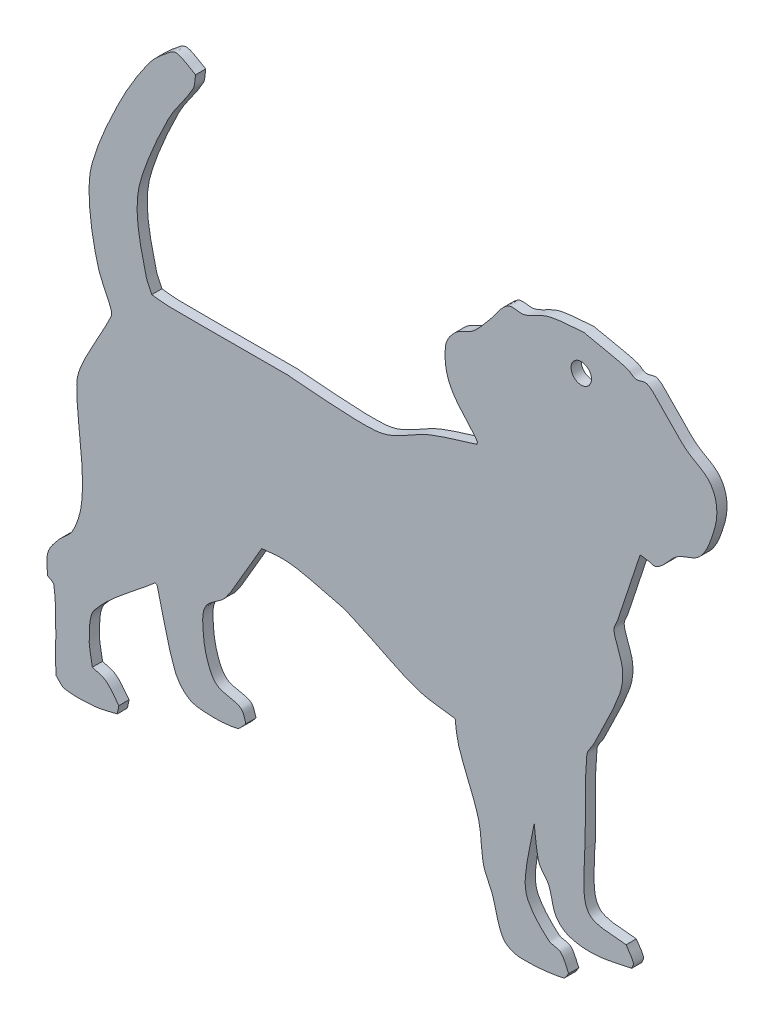
SolidWorks part; units mm, degrees
material "Custom Plastic"
ref_plane "Front Plane" through (0, 0, 0) normal (0, 0, 1) x (1, 0, 0)
ref_plane "Top Plane" through (0, 0, 0) normal (0, 1, 0) x (1, 0, 0)
ref_plane "Right Plane" through (0, 0, 0) normal (1, 0, 0) x (0, 0, -1)
sketch "Sketch1" plane through (0, 0, 0) normal (0, 0, 1) x (1, 0, 0)
  line L0 (320, 883) -> (1600, 883) construction
  line L1 (430, 467) -> (425, 468)
  line L2 (335, 158) -> (331, 138)
  spline S0 degree 3 poles (157, 350) (157.3333, 366.6667) (153.3255, 383.9988) (158, 400) (162.3301, 414.8221) (173.3915, 426.9119) (183, 439) (194.1503, 453.0279) (211.409, 462.2741) (220, 478) (231.5736, 499.1856) (238.9889, 523.0477) (242, 547) (246.5737, 583.3818) (244.0243, 620.4567) (241, 657) (237.1118, 703.9822) (229.509, 750.8597) (230, 798) (230.1827, 815.5426) (235.7972, 833.0032) (243, 849) (264.6078, 896.9895) (293.9451, 941.2143) (316, 989) (318.2393, 993.8519) (316.8218, 999.9764) (315, 1005) (305.7338, 1030.5522) (290.1289, 1053.7711) (283, 1080) (272.3494, 1119.1863) (264.8394, 1159.4915) (262, 1200) (259.8047, 1231.3203) (259.4994, 1263.7756) (268, 1294) (283.787, 1350.1317) (308.2885, 1403.6653) (334, 1456) (355.4262, 1499.6122) (380.5007, 1541.6439) (409, 1581) (422.8269, 1600.0943) (441.5162, 1615.367) (460, 1630) (465.8731, 1634.6495) (473.6955, 1639.6601) (481, 1638) (497.4268, 1634.2666) (511, 1622.6667) (526, 1615) knots 0 0 0 0 1 1 1 2 2 2 3 3 3 4 4 4 5 5 5 6 6 6 7 7 7 8 8 8 9 9 9 10 10 10 11 11 11 12 12 12 13 13 13 14 14 14 15 15 15 16 16 16 17 17 17 17
  spline S1 degree 3 poles (526, 1615) (524, 1604) (525.1849, 1591.9054) (520, 1582) (502.5479, 1548.6586) (475.8299, 1520.6597) (459, 1487) (432.3392, 1433.6783) (407.6914, 1378.9299) (390, 1322) (381.4465, 1294.4752) (379.1669, 1264.7649) (381, 1236) (383.5446, 1196.0699) (393.6625, 1156.9063) (403, 1118) (405.7171, 1106.6787) (412.3333, 1096.6667) (417, 1086) knots 0 0 0 0 1 1 1 2 2 2 3 3 3 4 4 4 5 5 5 6 6 6 6
  spline S2 degree 3 poles (417, 1086) (430, 1084.6667) (442.9327, 1082.1533) (456, 1082) (556.6597, 1080.8192) (657.3339, 1082.329) (758, 1082) (759.3744, 1081.9955) (760.6274, 1081.0702) (762, 1081) (832.3203, 1077.4022) (902.6992, 1067.0394) (973, 1071) (1022.6427, 1073.7968) (1063.7124, 1111.843) (1110, 1130) (1148.1735, 1144.9742) (1188, 1155.3333) (1227, 1168) knots 0 0 0 0 1 1 1 2 2 2 3 3 3 4 4 4 5 5 5 6 6 6 6
  spline S3 degree 3 poles (1227, 1168) (1227.3333, 1170.3333) (1229.3585, 1173.0738) (1228, 1175) (1206.6346, 1205.2942) (1175.93, 1229.5268) (1160, 1263) (1148.7167, 1286.7093) (1146.1485, 1314.898) (1149, 1341) (1150.7197, 1356.7423) (1161.6412, 1370.9657) (1173, 1382) (1185.7529, 1394.3885) (1205.2893, 1397.6807) (1219, 1409) (1234.2854, 1421.6193) (1245.8602, 1438.1597) (1259, 1453) (1274.1956, 1470.1621) (1284.5241, 1492.9115) (1304, 1505) (1315.9084, 1512.3914) (1332.4841, 1503.2898) (1346, 1507) (1367.0195, 1512.77) (1384.8286, 1527.8152) (1406, 1533) (1434.3531, 1539.9436) (1463.9508, 1540.127) (1493, 1543) (1494.3677, 1543.1353) (1495.6551, 1542.2831) (1497, 1542) (1520.9894, 1536.9496) (1545.0899, 1532.4136) (1569, 1527) (1580.4343, 1524.4111) (1592.0061, 1522.0718) (1603, 1518) (1610.1348, 1515.3575) (1615.4909, 1508.226) (1623, 1507) (1632.5913, 1505.4341) (1643.1481, 1514.011) (1652, 1510) (1666.3987, 1503.4756) (1675.5844, 1488.9349) (1687, 1478) (1707.2559, 1458.597) (1725.497, 1437.0111) (1747, 1419) (1764.6486, 1404.2174) (1788.2409, 1396.7824) (1804, 1380) (1814.821, 1368.4763) (1821.6551, 1352.633) (1824, 1337) (1826.8293, 1318.1381) (1824.5313, 1298.2533) (1819, 1280) (1810.9992, 1253.5974) (1802.3044, 1225.6412) (1784, 1205) (1769.2599, 1188.3782) (1743.0901, 1186.8959) (1725, 1174) (1709.0689, 1162.6432) (1699.0859, 1144.1364) (1683, 1133) (1666.1354, 1121.3245) (1666.2267, 1128.4267) (1656, 1130) (1648.6849, 1131.1254) (1641.3333, 1132) (1634, 1133) knots 0 0 0 0 1 1 1 2 2 2 3 3 3 4 4 4 5 5 5 6 6 6 7 7 7 8 8 8 9 9 9 10 10 10 11 11 11 12 12 12 13 13 13 14 14 14 15 15 15 16 16 16 17 17 17 18 18 18 19 19 19 20 20 20 21 21 21 22 22 22 23 23 23 24 24 24 25 25 25 25
  spline S4 degree 3 poles (1634, 1133) (1615.3333, 1076.6667) (1596.6805, 1020.3288) (1578, 964) (1575.0138, 954.9954) (1567.8697, 946.4193) (1569, 937) (1572.0168, 911.8602) (1587.2889, 889.1746) (1590, 864) (1592.0497, 844.9673) (1589.5198, 824.9982) (1583, 807) (1565.6271, 759.0409) (1540.8476, 714.0931) (1519, 668) (1513.5075, 656.4122) (1502.1853, 646.7687) (1501, 634) (1494.7444, 566.6099) (1498.6343, 498.6601) (1497, 431) (1496.9668, 429.626) (1496.0125, 428.3743) (1496, 427) (1495.6788, 391.6681) (1490.7586, 355.9424) (1496, 321) (1497.976, 307.8265) (1504.8812, 292.5299) (1517, 287) (1542.1773, 275.5113) (1571.6667, 278.3333) (1599, 274) knots 0 0 0 0 1 1 1 2 2 2 3 3 3 4 4 4 5 5 5 6 6 6 7 7 7 8 8 8 9 9 9 10 10 10 11 11 11 11
  spline S5 degree 3 poles (1599, 274) (1605, 264) (1613.4641, 255.1129) (1617, 244) (1618.4716, 239.3751) (1614.3333, 234.6667) (1613, 230) knots 0 0 0 0 1 1 1 2 2 2 2
  spline S6 degree 3 poles (1613, 230) (1583, 224.6667) (1553.4192, 215.7663) (1523, 214) (1501.2447, 212.7368) (1478.6525, 214.0456) (1458, 221) (1444.7283, 225.4691) (1432.2459, 235.0164) (1425, 247) (1414.1452, 264.9523) (1414.5758, 287.8541) (1406, 307) (1400.1044, 320.1622) (1386.343, 329.2472) (1382, 343) (1374.0785, 368.0848) (1374, 395) (1370, 421) knots 0 0 0 0 1 1 1 2 2 2 3 3 3 4 4 4 5 5 5 6 6 6 6
  spline S7 degree 3 poles (1370, 421) (1362.6667, 379) (1351.3808, 337.5012) (1348, 295) (1346.6616, 278.1745) (1348.0143, 259.87) (1356, 245) (1368.0768, 222.5121) (1386.6708, 203.6714) (1406, 187) (1414.0655, 180.0435) (1428.2394, 183.295) (1436, 176) (1446.0022, 166.5979) (1449.3333, 152) (1456, 140) knots 0 0 0 0 1 1 1 2 2 2 3 3 3 4 4 4 5 5 5 5
  spline S8 degree 3 poles (1456, 140) (1451.3333, 134.6667) (1448.918, 125.5373) (1442, 124) (1408.3267, 116.517) (1373.4913, 113.5108) (1339, 114) (1325.7181, 114.1884) (1311.8356, 118.3166) (1301, 126) (1292.3244, 132.1518) (1287.8548, 143.0878) (1284, 153) (1276.0841, 173.3553) (1273.175, 195.3719) (1266, 216) (1259.817, 233.7762) (1248.3875, 249.6978) (1244, 268) (1236.626, 298.76) (1239.299, 331.4765) (1231, 362) (1219.5154, 404.24) (1199.2228, 443.6016) (1185, 485) (1177.9476, 505.5274) (1174.8025, 527.3699) (1173, 549) knots 0 0 0 0 1 1 1 2 2 2 3 3 3 4 4 4 5 5 5 6 6 6 7 7 7 8 8 8 9 9 9 9
  spline S9 degree 3 poles (1173, 549) (1141.6667, 554.3333) (1109.1529, 554.949) (1079, 565) (1034.5613, 579.8129) (993.8594, 604.0979) (951, 623) (928.8531, 632.7674) (907.5245, 645.3002) (884, 651) (777.6658, 676.7638) (763.6901, 685.0262) (691, 675) knots 0 0 0 0 1 1 1 2 2 2 3 3 3 4 4 4 4
  spline S10 degree 3 poles (691, 675) (672.0513, 643.1662) (654.1442, 610.7166) (635, 579) (623.3872, 559.7609) (613.4699, 539.1937) (599, 522) (584.8651, 505.2044) (559.5993, 497.7419) (550, 478) (540.5076, 458.4778) (544.255, 434.6374) (546, 413) (547.6248, 392.8527) (552.4932, 372.7671) (560, 354) (564.7059, 342.2352) (571.2705, 329.7404) (582, 323) (598.603, 312.5699) (621.468, 315.5422) (638, 305) (646.1699, 299.7902) (647.4014, 287.9966) (651, 279) (651.5104, 277.7239) (650.9718, 275.9718) (650, 275) (643.1484, 268.1484) (637.406, 258.3273) (628, 256) (603.6779, 249.9822) (578.0247, 249.7591) (553, 251) (537.2537, 251.7808) (520.0155, 253.1033) (507, 262) (492.0839, 272.1958) (480.3531, 288.086) (474, 305) (454.3244, 357.383) (444.6667, 413) (430, 467) knots 0 0 0 0 1 1 1 2 2 2 3 3 3 4 4 4 5 5 5 6 6 6 7 7 7 8 8 8 9 9 9 10 10 10 11 11 11 12 12 12 13 13 13 14 14 14 14
  spline S11 degree 3 poles (425, 468) (375, 423.6667) (317.2453, 386.7762) (275, 335) (260.3699, 317.0692) (262.0921, 290.1163) (261, 267) (260.0634, 247.1755) (266.3333, 227.6667) (269, 208) knots 0 0 0 0 1 1 1 2 2 2 3 3 3 3
  spline S12 degree 3 poles (269, 208) (280.3333, 203.6667) (293.3285, 202.3269) (303, 195) (315.9975, 185.1534) (324.3333, 170.3333) (335, 158) knots 0 0 0 0 1 1 1 2 2 2 2
  spline S13 degree 3 poles (331, 138) (312, 134) (293.3484, 127.6247) (274, 126) (249.4176, 123.9358) (224.1995, 122.2105) (200, 127) (190.7052, 128.8396) (185.3333, 139) (178, 145) knots 0 0 0 0 1 1 1 2 2 2 3 3 3 3
  spline S14 degree 3 poles (178, 145) (177.6667, 170) (177, 194.9978) (177, 220) (177, 221.3744) (178.047, 222.6264) (178, 224) (176.7117, 261.6815) (179.1984, 299.8095) (173, 337) (171.8703, 343.7783) (162.3333, 345.6667) (157, 350) knots 0 0 0 0 1 1 1 2 2 2 3 3 3 4 4 4 4
extrude "Boss-Extrude1" add sketch "Sketch1" along normal blind 25.4
sketch "Sketch2" plane through (0, 0, 0) normal (0, 0, -1) x (-1, 0, 0)
  circle A0 centre (-1487.3431, 1451.337) radius 25.4
  dimension "D1" = 50.8
  dimension "D2" = 146.6569
  dimension "D3" = 1311.337
extrude "Cut-Extrude1" cut sketch "Sketch2" against normal blind 25.4
